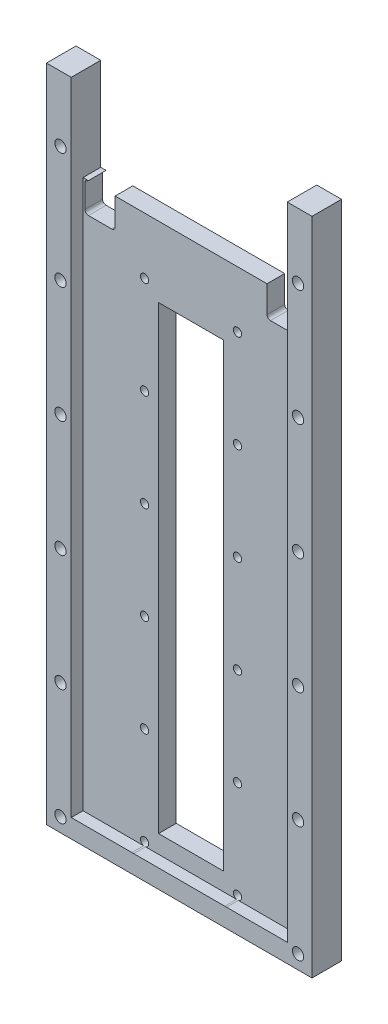
SolidWorks part; units mm, degrees
ref_plane "Front Plane" through (0, 0, 0) normal (0, 0, 1) x (1, 0, 0)
ref_plane "Top Plane" through (0, 0, 0) normal (0, 1, 0) x (1, 0, 0)
ref_plane "Right Plane" through (0, 0, 0) normal (1, 0, 0) x (0, 0, -1)
sketch "Sketch1" plane through (0, 0, 0) normal (0, 0, 1) x (1, 0, 0)
  line L1 (-28.575, -71.247) -> (28.575, -71.247)
  line L2 (-28.575, -71.247) -> (-28.575, 71.247)
  line L3 (-28.575, 71.247) -> (28.575, 71.247)
  line L4 (28.575, -71.247) -> (28.575, 71.247)
  line L5 (-28.575, -71.247) -> (28.575, 71.247) construction
  line L6 (-28.575, 71.247) -> (28.575, -71.247) construction
  point P0 (0, 0)
  dimension "D1" = 142.494
  dimension "D2" = 57.15
extrude "Boss-Extrude1" add sketch "Sketch1" along normal blind 6.35
sketch "Sketch2" plane through (0, 0, 6.35) normal (0, 0, 1) x (1, 0, 0)
  line L0 (0, -71.247) -> (0, 71.247) construction
  line L1 (-28.575, -71.247) -> (28.575, -71.247) construction
  line L2 (28.575, 71.247) -> (-28.575, 71.247) construction
  line L4 (-7, 35.6202) -> (7, 35.6202)
  line L5 (-7, 35.6202) -> (-7, -63.3798)
  line L6 (-7, -63.3798) -> (7, -63.3798)
  line L7 (7, 35.6202) -> (7, -63.3798)
  line L8 (-7, 35.6202) -> (7, -63.3798) construction
  line L9 (-7, -63.3798) -> (7, 35.6202) construction
  point P6 (0, -13.8798)
  dimension "D1" = 14
  dimension "D2" = 99
extrude "Cut-Extrude1" cut sketch "Sketch2" against normal through all
sketch "Sketch3" plane through (0, 0, 6.35) normal (0, 0, 1) x (1, 0, 0)
  line L0 (-28.575, 71.247) -> (-28.575, -71.247) construction
  line L1 (-28.575, -71.247) -> (28.575, -71.247) construction
  circle A0 centre (-25.575, -68.247) radius 1.2192
  dimension "D3" = 2.4384
  dimension "D1" = 3
  dimension "D2" = 3
extrude "Cut-Extrude2" cut sketch "Sketch3" against normal through all
mirror "Mirror1" about plane through (0, 0, 0) normal (1, 0, 0) of "Cut-Extrude2"
pattern_linear "LPattern1" count 6 spacing 25 along (0, 1, 0) of "Mirror1", "Cut-Extrude2"
sketch "Sketch4" plane through (0, 0, 6.35) normal (0, 0, 1) x (1, 0, 0)
  line L0 (-7, -63.3798) -> (7, -63.3798) construction
  line L1 (-7, 35.6202) -> (-7, -63.3798) construction
  circle A0 centre (-10, -66.3798) radius 0.889
  dimension "D1" = 1.778
  dimension "D2" = 3
  dimension "D3" = 3
extrude "Cut-Extrude3" cut sketch "Sketch4" against normal through all
mirror "Mirror2" about plane through (0, 0, 0) normal (1, 0, 0) of "Cut-Extrude3"
pattern_linear "LPattern2" count 6 spacing 21 along (0, 1, 0) of "Mirror2", "Cut-Extrude3"
sketch "Sketch6" plane through (0, 0, 6.35) normal (0, 0, 1) x (1, 0, 0)
  line L0 (0, 35.6202) -> (0, 71.247) construction
  line L1 (7, 35.6202) -> (-7, 35.6202) construction
  line L2 (28.575, 71.247) -> (-28.575, 71.247) construction
  line L4 (-20.955, 50.7938) -> (20.955, 50.7938)
  line L5 (-20.955, 50.7938) -> (-20.955, 60.9538)
  line L6 (-20.955, 60.9538) -> (20.955, 60.9538)
  line L7 (20.955, 50.7938) -> (20.955, 60.9538)
  line L8 (-20.955, 50.7938) -> (20.955, 60.9538) construction
  line L9 (-20.955, 60.9538) -> (20.955, 50.7938) construction
  point P6 (0, 55.8738)
  point P11 (0, 55.8738)
  dimension "D1" = 41.91
  dimension "D2" = 10.16
extrude "Cut-Extrude4" cut sketch "Sketch6" against normal through all
sketch "Sketch8" plane through (0, 0, 6.35) normal (0, 0, 1) x (1, 0, 0)
  line L1 (-23.25, -67.247) -> (23.25, -67.247)
  line L2 (-23.25, -67.247) -> (-23.25, 85.153)
  line L3 (-23.25, 85.153) -> (23.25, 85.153)
  line L4 (23.25, -67.247) -> (23.25, 85.153)
  line L5 (-23.25, -67.247) -> (23.25, 85.153) construction
  line L6 (-23.25, 85.153) -> (23.25, -67.247) construction
  line L7 (-28.575, -71.247) -> (28.575, -71.247) construction
  point P0 (0, 8.953)
  point P5 (0, 0)
  point P7 (0, -3.5067)
  point P8 (0, 8.082)
  dimension "D1" = 46.5
  dimension "D2" = 152.4
  dimension "D3" = 4
extrude "Cut-Extrude6" cut sketch "Sketch8" against normal blind 2.54
sketch "Sketch9" plane through (0, 71.247, 0) normal (0, 1, 0) x (1, 0, 0)
  line L1 (-28.575, -6.35) -> (28.575, -6.35)
  line L2 (-28.575, -6.35) -> (-28.575, 0)
  line L3 (-28.575, 0) -> (28.575, 0)
  line L4 (28.575, -6.35) -> (28.575, 0)
extrude "Cut-Extrude7" cut sketch "Sketch9" against normal blind 0.5
sketch "Sketch11" plane through (0, 0, 0) normal (0, 0, -1) x (-1, 0, 0)
  line L0 (0, 35.6202) -> (0, 50.7938) construction
  line L1 (-22.85, 44.2938) -> (-16.35, 44.2938)
  line L2 (-22.85, 44.2938) -> (-22.85, 50.7938)
  line L3 (-22.85, 50.7938) -> (-16.35, 50.7938)
  line L4 (-16.35, 44.2938) -> (-16.35, 50.7938)
  line L5 (-22.85, 44.2938) -> (-16.35, 50.7938) construction
  line L6 (-22.85, 50.7938) -> (-16.35, 44.2938) construction
  line L7 (-7, 35.6202) -> (7, 35.6202) construction
  line L8 (20.955, 50.7938) -> (-20.955, 50.7938) construction
  point P0 (-19.6, 47.5438)
  point P11 (-19.6, 46.8998)
  dimension "D1" = 6.5
  dimension "D2" = 19.6
extrude "Cut-Extrude8" cut sketch "Sketch11" against normal through all
fillet "Fillet1" radius 0.75 3 edges at (22.85, 44.2938, 1.905) (16.35, 44.2938, 1.905) (22.85, 50.7938, 1.905)
mirror "Mirror4" about plane through (0, 0, 0) normal (1, 0, 0) of "Cut-Extrude8", "Fillet1"
sketch "Sketch12" plane through (0, 0, 3.81) normal (0, 0, 1) x (1, 0, 0)
  line L0 (23.25, 70.747) -> (-23.25, 70.747) construction
  line L1 (-20.955, 60.9538) -> (20.955, 60.9538)
  line L2 (-20.955, 60.9538) -> (-20.955, 70.747)
  line L3 (-20.955, 70.747) -> (20.955, 70.747)
  line L4 (20.955, 60.9538) -> (20.955, 70.747)
extrude "Cut-Extrude9" cut sketch "Sketch12" against normal through all
sketch "Sketch13" plane through (0, 0, 3.81) normal (0, 0, 1) x (1, 0, 0)
  line L0 (23.25, -67.247) -> (23.25, 70.747) construction
  line L1 (-23.25, 70.747) -> (23.25, 70.747)
  line L2 (-23.25, 70.747) -> (-23.25, 50.7938)
  line L3 (-23.25, 50.7938) -> (23.25, 50.7938)
  line L4 (23.25, 70.747) -> (23.25, 50.7938)
extrude "Cut-Extrude10" cut sketch "Sketch13" against normal through all
